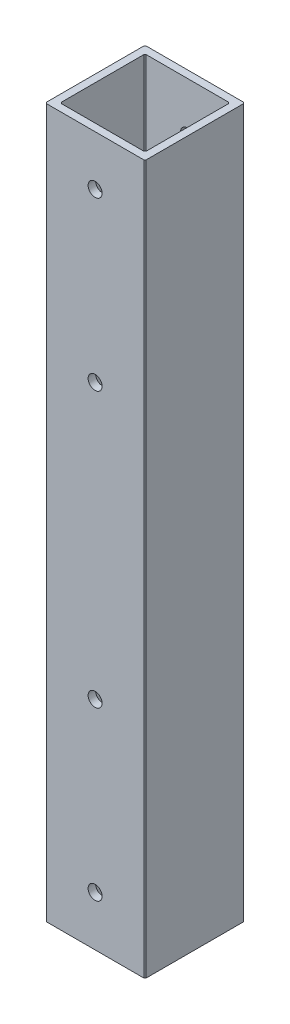
SolidWorks part; units mm, degrees
ref_plane "Front Plane" through (0, 0, 0) normal (0, 0, 1) x (1, 0, 0)
ref_plane "Top Plane" through (0, 0, 0) normal (0, 1, 0) x (1, 0, 0)
ref_plane "Right Plane" through (0, 0, 0) normal (1, 0, 0) x (0, 0, -1)
ref_plane "Plane1" through (-210, 0, 0) normal (-1, 0, 0) x (0, -1, 0)
sketch "Sketch1" plane through (-210, 0, 0) normal (-1, 0, 0) x (0, -1, 0)
  line L0 (-142, 180) -> (-142, 140)
  line L1 (-142, 140) -> (142, 140)
  line L2 (142, 140) -> (142, 180)
  line L3 (142, 180) -> (-142, 180)
extrude "Boss-Extrude1" add sketch "Sketch1" against normal blind 40
sketch "Sketch2" plane through (0, -142, 0) normal (0, -1, 0) x (1, 0, 0)
  line L0 (-173, 143) -> (-173, 177)
  line L1 (-173, 177) -> (-207, 177)
  line L2 (-207, 177) -> (-207, 143)
  line L3 (-207, 143) -> (-173, 143)
extrude "Cut-Extrude1" cut sketch "Sketch2" against normal through all
hole_wizard "Ø5.6 (5.6) Diameter Hole1" positions "Sketch4" profile "Sketch3" hole size "Ø5.6" standard "ANSI Metric"
sketch "Sketch4" plane through (0, 0, 140) normal (0, 0, -1) x (-1, 0, 0)
  point P0 (190, 122)
  point P1 (190, 55)
  point P2 (190, -55)
  point P3 (190, -122)
sketch "Sketch3" plane through (-190, 122, 140) normal (1, 0, 0) x (0, 1, 0)
  line L0 (0, 0) -> (0, 3)
  line L1 (0, 3) -> (2.8, 3)
  line L2 (2.8, 3) -> (2.8, 0)
  line L5 (2.8, 0) -> (0, 0)
  line L11 (0, -6.35) -> (0, 107.95) construction
  dimension "Thru Hole Dia." = 5.6
  dimension "Thru Hole Depth" = 3
hole_wizard "Ø5.6 (5.6) Diameter Hole2" positions "Sketch6" profile "Sketch5" hole size "Ø5.6" standard "ANSI Metric"
sketch "Sketch6" plane through (0, 0, 177) normal (0, 0, -1) x (-1, 0, 0)
  point P0 (190, 122)
  point P1 (190, 55)
  point P2 (190, -55)
  point P3 (190, -122)
sketch "Sketch5" plane through (-190, 122, 177) normal (1, 0, 0) x (0, 1, 0)
  line L0 (0, 0) -> (0, 3)
  line L1 (0, 3) -> (2.8, 3)
  line L2 (2.8, 3) -> (2.8, 0)
  line L5 (2.8, 0) -> (0, 0)
  line L11 (0, -6.35) -> (0, 107.95) construction
  dimension "Thru Hole Dia." = 5.6
  dimension "Thru Hole Depth" = 3
chamfer "Chamfer1" distance 0.5 angle 45 8 edges at (-170, 0, 140) (-210, 0, 140) (-210, 0, 180) (-207, 0, 177) (-170, 0, 180) (-173, 0, 143) (-173, 0, 177) (-207, 0, 143)
